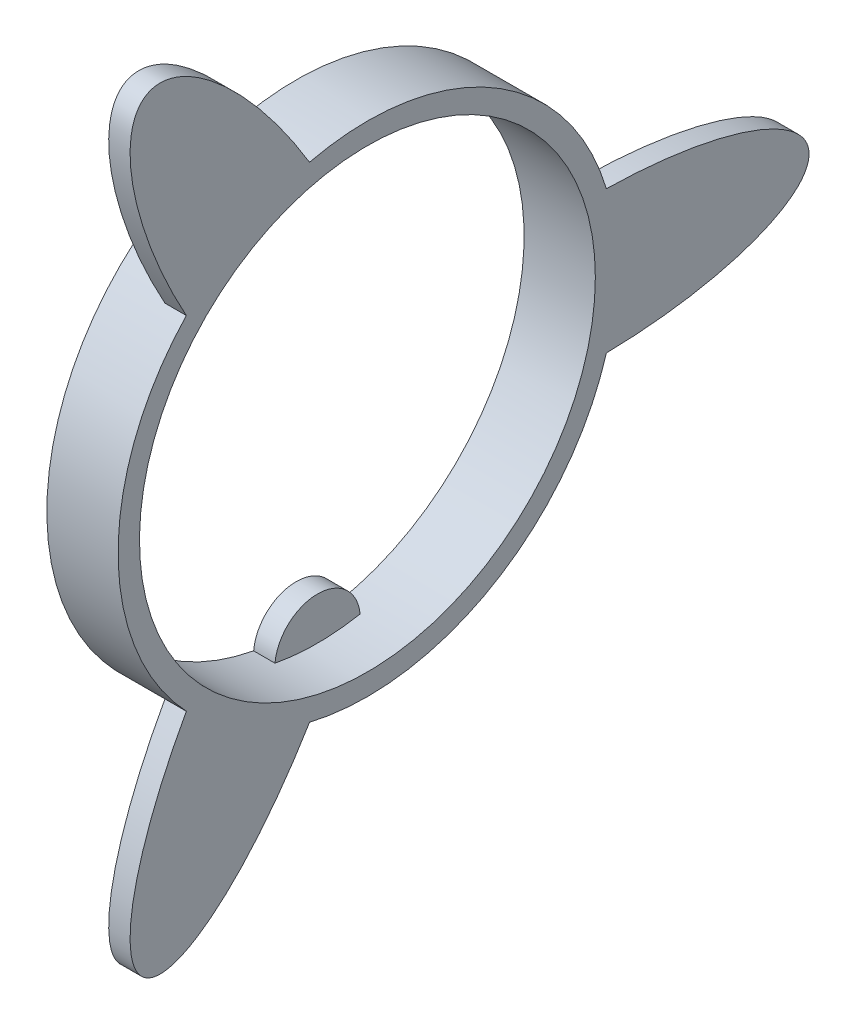
SolidWorks part; units mm, degrees
ref_plane "Front Plane" through (0, 0, 0) normal (0, 0, 1) x (1, 0, 0)
ref_plane "Top Plane" through (0, 0, 0) normal (0, 1, 0) x (1, 0, 0)
ref_plane "Right Plane" through (0, 0, 0) normal (1, 0, 0) x (0, 0, -1)
sketch "Sketch1" plane through (0, 0, 0) normal (1, 0, 0) x (0, 0, -1)
  circle A0 centre (0, 0) radius 17.5
  circle A1 centre (0, 0) radius 16
extrude "Boss-Extrude1" add sketch "Sketch1" along normal blind 5
sketch "Sketch2" plane through (5, 0, 0) normal (1, 0, 0) x (0, 0, -1)
  line L0 (0, 0) -> (-8, 13.8564)
  line L5 (0, 0) -> (16, 0)
  line L6 (0, 0) -> (-8, -13.8564)
  line L7 (2.75, 0) -> (-2.75, 0) construction
  ellipse E0 centre (-8, -13.8564) end of major axis (-15.5, -26.8468) minor radius 5
  ellipse E1 centre (-8, 13.8564) end of major axis (-0.5, 0.866) minor radius 5
  ellipse E2 centre (16, 0) end of major axis (1, 0) minor radius 5
  circle M11 centre (0, 0) radius 17.5
extrude "Boss-Extrude2" add sketch "Sketch2" against normal blind 1.5 contours E1 M11 | E2 M11 | E0 M11
sketch "Sketch3" plane through (0, 0, 0) normal (-1, 0, 0) x (0, 0, 1)
  line L0 (2.75, 0) -> (-2.75, 0) construction
  line L1 (3, -16) -> (-3, -16)
  line L2 (3, 16) -> (-3, 16)
  arc A2 (3, -16) -> (-3, -16) centre (0, -16) ccw
  arc A3 (3, 16) -> (-3, 16) centre (0, 16) cw
extrude "Boss-Extrude3" add sketch "Sketch3" against normal blind 1.5
